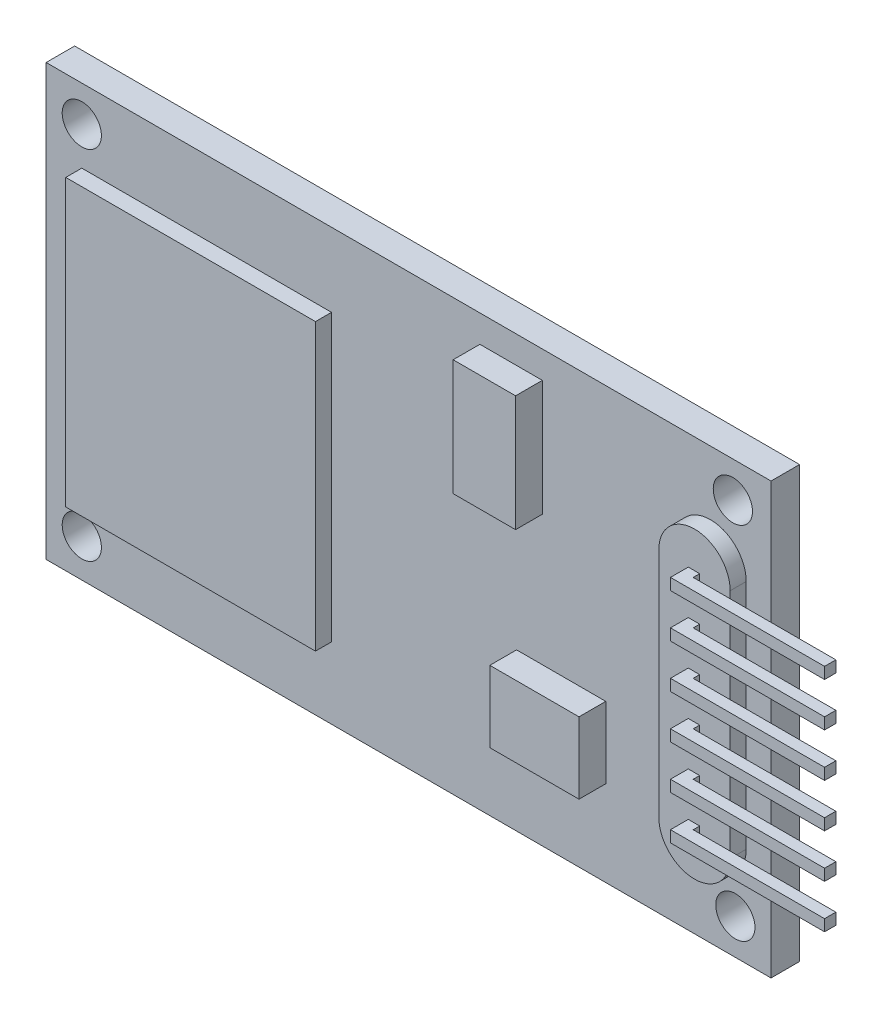
SolidWorks part; units mm, degrees
ref_plane "Front Plane" through (0, 0, 0) normal (0, 0, 1) x (1, 0, 0)
ref_plane "Top Plane" through (0, 0, 0) normal (0, 1, 0) x (1, 0, 0)
ref_plane "Right Plane" through (0, 0, 0) normal (1, 0, 0) x (0, 0, -1)
sketch "Sketch1" plane through (0, 0, 0) normal (0, 0, 1) x (1, 0, 0)
  line L1 (0, 0) -> (40.64, 0)
  line L2 (0, 0) -> (0, 24.13)
  line L3 (0, 24.13) -> (40.64, 24.13)
  line L4 (40.64, 0) -> (40.64, 24.13)
  dimension "D1" = 40.64
  dimension "D2" = 24.13
extrude "Boss-Extrude1" add sketch "Sketch1" along normal blind 1.6
sketch "Sketch2" plane through (0, 0, 0) normal (0, 0, 1) x (1, 0, 0)
  line L0 (0, 24.13) -> (0, 0) construction
  line L1 (2, 20) -> (16, 20)
  line L2 (2, 20) -> (2, 4)
  line L3 (2, 4) -> (16, 4)
  line L4 (16, 20) -> (16, 4)
  line L5 (0, 0) -> (40.64, 0) construction
  dimension "D1" = 14
  dimension "D2" = 16
  dimension "D3" = 2
  dimension "D4" = 4
extrude "Boss-Extrude2" add sketch "Sketch2" along normal blind 2.5 contours L2 L1 L4 L3
sketch "Sketch3" plane through (0, 0, 0) normal (0, 0, 1) x (1, 0, 0)
  line L0 (40.64, 24.13) -> (0, 24.13) construction
  line L1 (0, 24.13) -> (0, 0) construction
  circle A0 centre (2, 22.13) radius 1.1
  dimension "D1" = 2.2
  dimension "D2" = 2
  dimension "D3" = 2
extrude "Cut-Extrude1" cut sketch "Sketch3" along normal blind 2.5
pattern_linear "LPattern1" count 2 spacing 36.5 along (1, 0, 0) of "Cut-Extrude1"
pattern_linear "LPattern2" count 2 spacing 20 along (0, -1, 0) of "Cut-Extrude1"
sketch "Sketch4" plane through (0, 0, 1.6) normal (0, 0, 1) x (1, 0, 0)
  line L0 (0, 0) -> (40.64, 0) construction
  line L1 (40.64, 0) -> (40.64, 24.13) construction
  circle A0 centre (38.64, 2) radius 1.1
  dimension "D1" = 2.2
  dimension "D2" = 2
  dimension "D3" = 2
extrude "Cut-Extrude2" cut sketch "Sketch4" against normal blind 2.5
sketch "Sketch5" plane through (0, 0, 0) normal (0, 0, 1) x (1, 0, 0)
  line L0 (35.2493, 18.556) -> (35.2493, 5.556)
  line L1 (39.2493, 5.556) -> (39.2493, 18.556)
  arc A0 (35.2493, 18.556) -> (39.2493, 18.556) centre (37.2493, 18.556) cw
  arc A1 (39.2493, 5.556) -> (35.2493, 5.556) centre (37.2493, 5.556) cw
  circle A2 centre (38.64, 2) radius 1.1 construction
  dimension "D2" = 2
  dimension "D3" = 3.556
  dimension "D1" = 13
extrude "Boss-Extrude3" add sketch "Sketch5" along normal blind 2.5 contours A1 L0 A0 L1
sketch "Sketch6" plane through (0, 0, 2.5) normal (0, 0, 1) x (1, 0, 0)
  line L0 (35.2493, 18.556) -> (35.2493, 5.556) construction
  line L1 (36.9003, 18.5306) -> (37.5403, 18.5306)
  line L2 (36.9003, 18.5306) -> (36.9003, 17.8906)
  line L3 (36.9003, 17.8906) -> (37.5403, 17.8906)
  line L4 (37.5403, 18.5306) -> (37.5403, 17.8906)
  arc A0 (39.2493, 18.556) -> (35.2493, 18.556) centre (37.2493, 18.556) ccw construction
  dimension "D1" = 0.64
  dimension "D2" = 0.64
  dimension "D3" = 1.651
  dimension "D4" = 0.0254
extrude "Boss-Extrude4" add sketch "Sketch6" along normal blind 1
sketch "Sketch8" plane through (37.5403, 0, 0) normal (1, 0, 0) x (0, 0, -1)
  line L0 (-3.5, 17.8906) -> (-2.5, 17.8906) construction
  line L1 (-3.5, 18.5306) -> (-2.865, 18.5306)
  line L2 (-3.5, 18.5306) -> (-3.5, 17.8906)
  line L3 (-3.5, 17.8906) -> (-2.865, 17.8906)
  line L4 (-2.865, 18.5306) -> (-2.865, 17.8906)
  dimension "D1" = 0.635
extrude "Boss-Extrude5" add sketch "Sketch8" along normal blind 8
pattern_linear "LPattern7" count 6 spacing 2.45 along (0, -1, 0) of "Boss-Extrude4", "Boss-Extrude5"
sketch "Sketch9" plane through (0, 0, 1.6) normal (0, 0, 1) x (1, 0, 0)
  line L0 (40.64, 24.13) -> (0, 24.13) construction
  line L1 (24.3183, 22.606) -> (27.8183, 22.606)
  line L2 (24.3183, 22.606) -> (24.3183, 16.106)
  line L3 (24.3183, 16.106) -> (27.8183, 16.106)
  line L4 (27.8183, 22.606) -> (27.8183, 16.106)
  dimension "D1" = 6.5
  dimension "D2" = 3.5
  dimension "D3" = 1.524
extrude "Boss-Extrude6" add sketch "Sketch9" along normal blind 1.5
sketch "Sketch10" plane through (0, 0, 1.6) normal (0, 0, 1) x (1, 0, 0)
  line L1 (26.3747, 8.7986) -> (31.3747, 8.7986)
  line L2 (26.3747, 8.7986) -> (26.3747, 4.7986)
  line L3 (26.3747, 4.7986) -> (31.3747, 4.7986)
  line L4 (31.3747, 8.7986) -> (31.3747, 4.7986)
  dimension "D1" = 5
  dimension "D2" = 4
extrude "Boss-Extrude7" add sketch "Sketch10" along normal blind 1.5
